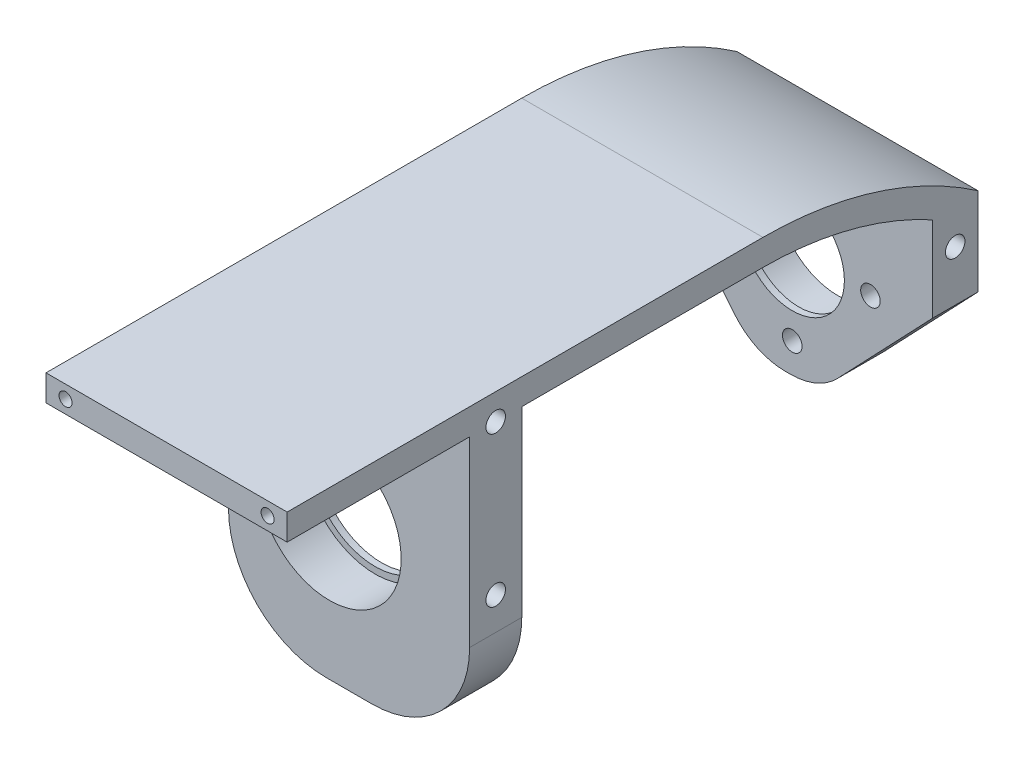
SolidWorks part; units mm, degrees
material "Polyetheretherketone (PEEK)"
ref_plane "Front Plane" through (0, 0, 0) normal (0, 0, 1) x (1, 0, 0)
ref_plane "Top Plane" through (0, 0, 0) normal (0, 1, 0) x (1, 0, 0)
ref_plane "Right Plane" through (0, 0, 0) normal (1, 0, 0) x (0, 0, -1)
sketch "Sketch3" plane through (0, 0, 0) normal (1, 0, 0) x (0, 0, -1)
  line L0 (0, 0) -> (73, 0)
  line L1 (0, 0) -> (0, -4)
  line L2 (0, -4) -> (73, -4)
  line L4 (113.6909, -22.5) -> (70.143, -22.5) construction
  line L6 (90.9961, -30.5) -> (104.9961, -30.5) construction
  line L7 (90.9961, -30.5) -> (90.9961, -14.5) construction
  line L8 (90.9961, -14.5) -> (104.9961, -14.5) construction
  line L9 (104.9961, -30.5) -> (104.9961, -14.5) construction
  line L10 (90.9961, -30.5) -> (104.9961, -14.5) construction
  line L11 (90.9961, -14.5) -> (104.9961, -30.5) construction
  line L13 (109.8205, -18.5) -> (115.4706, -18.5)
  arc A0 (73, 0) -> (115.4706, -18.5) centre (73, -58) cw
  arc A1 (73, -4) -> (104.9961, -14.5) centre (73, -58) cw
  arc A2 (104.9961, -14.5) -> (109.8205, -18.5) centre (73, -58) cw
  point P9 (97.9961, -22.5)
  dimension "D1" = 58
  dimension "D2" = 4
  dimension "D3" = 73
  dimension "D4" = 22.5
  dimension "D5" = 16
  dimension "D6" = 4
  dimension "D7" = 14
extrude "Boss-Extrude1" add sketch "Sketch3" along normal blind 37
ref_plane "Plane1" through (21.5, 0, 0) normal (1, 0, 0) x (0, 0, -1)
sketch "Sketch4" plane through (37, 0, 0) normal (1, 0, 0) x (0, 0, -1)
  line L0 (28, -4) -> (28, -14.5)
  line L1 (0, -4) -> (73, -4) construction
  line L2 (114.75, -23.7518) -> (114.75, -33.7153) construction
  line L3 (0, 0) -> (0, -4) construction
  line L4 (28, -4) -> (36, -4)
  line L5 (36, -4) -> (36, -15.5)
  line L6 (36, -15.5) -> (35, -15.5) construction
  line L7 (35, -15.5) -> (35, -14.5) construction
  line L8 (35, -14.5) -> (28, -14.5) construction
  line L9 (35, -15.5) -> (35, -25.5) construction
  line L10 (35, -25.5) -> (17.1507, -25.5) construction
  line L11 (28, -14.5) -> (28, -36.5)
  line L12 (36, -15.5) -> (36, -35.5)
  line L13 (28, -47) -> (36, -47)
  line L14 (28, -47) -> (28, -36.5)
  line L15 (36, -47) -> (36, -35.5)
  line L16 (73, 0) -> (0, 0) construction
  arc A0 (109.8205, -18.5) -> (73, -4) centre (73, -58) ccw construction
  point P22 (28, -25.5)
  point P23 (36, -25.5)
  dimension "D1" = 28
  dimension "D2" = 114.75
  dimension "D3" = 25.5
  dimension "D4" = 8
  dimension "D5" = 7
  dimension "D6" = 11.5
  dimension "D7" = 11
extrude "Boss-Extrude3" add sketch "Sketch4" against normal up to surface (37 mm away) contours L11 L14 L13 L15 L12 L5 L4 L0 up to face at (0, -6.1802, -62.4324)
sketch "Sketch5" plane through (0, 0, -28) normal (0, 0, 1) x (1, 0, 0)
  line L0 (37, -25.5) -> (21.5, -25.5) construction
  line L1 (37, -47) -> (37, -4) construction
  circle A0 centre (21.5, -25.5) radius 11
  dimension "D2" = 22
  dimension "D1" = 15.5
  dimension "D3" = 21.5
extrude "Cut-Extrude1" cut sketch "Sketch5" against normal blind 7
sketch "Sketch6" plane through (0, 0, -35) normal (0, 0, 1) x (1, 0, 0)
  circle A0 centre (21.5, -25.5) radius 10
  dimension "D1" = 20
extrude "Cut-Extrude2" cut sketch "Sketch6" against normal blind 7
sketch "Sketch7" plane through (37, 0, 0) normal (1, 0, 0) x (0, 0, -1)
  line L0 (36, -4) -> (99, -4) construction
  line L1 (99, -4) -> (99, -10.6714) construction
  line L2 (67.5, -4) -> (67.5, -25.5) construction
  line L3 (67.5, -25.5) -> (116.1248, -25.5) construction
  line L4 (99, -10.6714) -> (99, -16) construction
  line L5 (99, -16) -> (105, -16) construction
  line L6 (105, -16) -> (105, -17.5) construction
  line L7 (105, -17.5) -> (106, -17.5) construction
  line L8 (106, -17.5) -> (106, -15.2566) construction
  line L9 (99, -10.6714) -> (99, -47)
  line L10 (99, -47) -> (106, -47)
  line L11 (106, -47) -> (106, -15.2566)
  arc A0 (109.8205, -18.5) -> (73, -4) centre (73, -58) ccw construction
  arc A2 (106, -15.2566) -> (99, -10.6714) centre (73, -58) ccw
  dimension "D1" = 63
  dimension "D2" = 21.5
  dimension "D3" = 9.5
  dimension "D4" = 8
  dimension "D5" = 6
  dimension "D6" = 1
  dimension "D7" = 43
extrude "Boss-Extrude4" add sketch "Sketch7" against normal up to surface (37 mm away) contours L11 A2 L9 L10 up to face at (0, -13.9081, -50.2594)
sketch "Sketch8" plane through (0, 0, -106) normal (0, 0, 1) x (1, 0, 0)
  circle A0 centre (21.5, -25.5) radius 9.5
  dimension "D1" = 19
extrude "Cut-Extrude3" cut sketch "Sketch8" along normal blind 6
sketch "Sketch9" plane through (0, 0, -100) normal (0, 0, -1) x (-1, 0, 0)
  circle A0 centre (-21.5, -25.5) radius 8
  dimension "D1" = 16
extrude "Cut-Extrude4" cut sketch "Sketch9" against normal blind 1
sketch "Sketch10" plane through (0, 0, -106) normal (0, 0, -1) x (-1, 0, 0)
  line L0 (0, -23.7577) -> (-17.4711, -42.0819)
  line L1 (0, -47) -> (0, -15.2566) construction
  line L2 (-17.4711, -42.0819) -> (-27.3185, -42.0819)
  line L3 (-27.3185, -42.0819) -> (-37, -30.2284)
  line L4 (-37, -47) -> (-37, -15.2566) construction
  line L5 (-37, -30.2284) -> (-37, -47)
  line L6 (-37, -47) -> (0, -47)
  line L7 (0, -47) -> (0, -23.7577)
extrude "Cut-Extrude5" cut sketch "Sketch10" against normal up to surface (7 mm away) up to face at (13.5, -25.5, -99)
sketch "Sketch11" plane through (37, 0, 0) normal (1, 0, 0) x (0, 0, -1)
  line L0 (106, -15.2566) -> (106, -10.303)
  line L1 (109.8205, -18.5) -> (115.4706, -18.5) construction
  line L2 (109.8205, -18.5) -> (115.4706, -18.5)
  arc A0 (115.4706, -18.5) -> (73, 0) centre (73, -58) ccw construction
  arc A1 (109.8205, -18.5) -> (106, -15.2566) centre (73, -58) ccw construction
  arc A2 (109.8205, -18.5) -> (106, -15.2566) centre (73, -58) ccw
  arc A3 (115.4706, -18.5) -> (106, -10.303) centre (73, -58) ccw
extrude "Cut-Extrude6" cut sketch "Sketch11" against normal through all
fillet "Fillet2" radius 10 2 edges at (17.4711, -42.0819, -102.5) (27.3185, -42.0819, -102.5)
sketch "Sketch12" plane through (0, 0, -99) normal (0, 0, 1) x (1, 0, 0)
  line L0 (21.5, -25.5) -> (21.5, -13.5) construction
  circle A0 centre (21.5, -13.5) radius 1.5
  circle A1 centre (33.5, -25.5) radius 1.5
  circle A2 centre (21.5, -37.5) radius 1.5
  circle A3 centre (9.5, -25.5) radius 1.5
  point P12 (21.5, -25.5)
  dimension "D1" = 3
  dimension "D3" = 12
  dimension "D4" = 12
  dimension "D5" = 12
  dimension "D2" = 4
extrude "Cut-Extrude7" cut sketch "Sketch12" against normal through all
sketch "Sketch13" [suppressed] plane through (0, 0, -28) normal (0, 0, 1) x (1, 0, 0)
  line L0 (23, 0) -> (23, -32) construction
  line L1 (37, 0) -> (0, 0) construction
  line L3 (0, -47) -> (0, -4) construction
  circle A0 centre (23, -32) radius 11
  dimension "D2" = 22
  dimension "D1" = 32
  dimension "D3" = 23
extrude "Cut-Extrude8" [suppressed] cut sketch "Sketch13" against normal blind 7 contours A0
sketch "Sketch14" [suppressed] plane through (0, 0, -35) normal (0, 0, 1) x (1, 0, 0)
  circle A0 centre (23, -32) radius 10
  dimension "D1" = 20
extrude "Cut-Extrude9" [suppressed] cut sketch "Sketch14" against normal blind 7
sketch "Sketch15" [suppressed] plane through (0, 0, 0) normal (-1, 0, 0) x (0, 0, 1)
  line L0 (-94, -8.2506) -> (-94, -47)
  line L1 (-94, -47) -> (-101, -47)
  line L2 (-101, -47) -> (-101, -11.8264)
  line L3 (-36, -4) -> (-36, -47) construction
  line L4 (-28, -47) -> (-36, -47) construction
  arc A0 (-73, -4) -> (-109.8205, -18.5) centre (-73, -58) ccw construction
  arc A1 (-94, -8.2506) -> (-101, -11.8264) centre (-73, -58) ccw
  dimension "D1" = 58
  dimension "D2" = 7
extrude "Boss-Extrude5" [suppressed] add sketch "Sketch15" against normal up to surface (37 mm away)
sketch "Sketch16" [suppressed] plane through (0, 0, -94) normal (0, 0, 1) x (1, 0, 0)
  circle A0 centre (23, -32) radius 8
  dimension "D1" = 16
extrude "Cut-Extrude10" [suppressed] cut sketch "Sketch16" against normal blind 1
sketch "Sketch17" [suppressed] plane through (0, 0, -95) normal (0, 0, 1) x (1, 0, 0)
  circle A0 centre (23, -32) radius 9.5
  dimension "D1" = 19
extrude "Cut-Extrude11" [suppressed] cut sketch "Sketch17" against normal through all
sketch "Sketch18" [suppressed] plane through (37, 0, 0) normal (1, 0, 0) x (0, 0, -1)
  line L0 (101, -11.8264) -> (101, -7.2063)
  line L1 (109.8205, -18.5) -> (115.4706, -18.5) construction
  line L2 (109.8205, -18.5) -> (115.4706, -18.5)
  arc A0 (115.4706, -18.5) -> (73, 0) centre (73, -58) ccw construction
  arc A1 (109.8205, -18.5) -> (101, -11.8264) centre (73, -58) ccw construction
  arc A2 (115.4706, -18.5) -> (101, -7.2063) centre (73, -58) ccw
  arc A3 (109.8205, -18.5) -> (101, -11.8264) centre (73, -58) ccw
extrude "Cut-Extrude12" [suppressed] cut sketch "Sketch18" against normal through all
sketch "Sketch19" [suppressed] plane through (0, 0, -101) normal (0, 0, -1) x (-1, 0, 0)
  line L0 (-23, -32) -> (-23, -20) construction
  circle A0 centre (-23, -20) radius 1.5
  circle A1 centre (-11, -32) radius 1.5
  circle A2 centre (-23, -44) radius 1.5
  circle A3 centre (-35, -32) radius 1.5
  point P12 (-23, -32)
  dimension "D1" = 3
  dimension "D2" = 12
  dimension "D4" = 12
  dimension "D5" = 12
  dimension "D3" = 4
extrude "Cut-Extrude13" [suppressed] cut sketch "Sketch19" against normal up to surface (7 mm away)
fillet "Fillet3" [suppressed] radius 10
fillet "Fillet4" [suppressed] radius 10
fillet "Fillet5" radius 15 2 edges at (0, -47, -32) (37, -47, -32)
sketch "Sketch20" plane through (0, 0, 0) normal (-1, 0, 0) x (0, 0, 1)
  line L0 (-28, -4) -> (-36, -4) construction
  line L1 (-99, -10.6714) -> (-106, -10.6714) construction
  line L2 (-106, -23.7577) -> (-106, -10.303) construction
  line L3 (-102.5, -10.6714) -> (-102.5, -16) construction
  line L4 (-73, 0) -> (0, 0) construction
  line L5 (-32, -4) -> (-32, 0) construction
  line L6 (-32, -32) -> (-32, -27) construction
  line L7 (-36, -32) -> (-28, -32) construction
  line L8 (0, 0) -> (0, -4) construction
  circle A0 centre (-32, -4) radius 1.5
  circle A1 centre (-102.5, -16) radius 1.5
  circle A2 centre (-32, -27) radius 1.5
  dimension "D1" = 3
  dimension "D2" = 3
  dimension "D5" = 3
  dimension "D3" = 16
  dimension "D4" = 5
  dimension "D6" = 23
  dimension "D7" = 32
  dimension "D8" = 102.5
extrude "Cut-Extrude14" cut sketch "Sketch20" against normal blind 6
sketch "Sketch21" plane through (0, 0, 0) normal (0, 0, 1) x (1, 0, 0)
  line L0 (0, 0) -> (0, -4) construction
  line L1 (0, -2) -> (3, -2) construction
  line L2 (37, -2) -> (34, -2) construction
  line L3 (37, 0) -> (37, -4) construction
  circle A0 centre (3, -2) radius 1
  circle A1 centre (34, -2) radius 1
  dimension "D2" = 2
  dimension "D4" = 2
  dimension "D1" = 3
  dimension "D3" = 3
  dimension "D5" = 31
extrude "Cut-Extrude15" cut sketch "Sketch21" against normal blind 6 contours A0 | A1
sketch "Sketch22" [suppressed] plane through (0, 0, 0) normal (-1, 0, 0) x (0, 0, 1)
  line L0 (-94, -8.2506) -> (-101, -8.2506) construction
  line L1 (-101, -7.2063) -> (-101, -37) construction
  line L2 (-36, -4) -> (-28, -4) construction
  line L3 (-73, 0) -> (0, 0) construction
  circle A0 centre (-97.5, -16) radius 1.5
  circle A1 centre (-32, -4) radius 1.5
  circle A2 centre (-32, -27) radius 1.5
  point P7 (-97.5, -8.2506)
  dimension "D2" = 3
  dimension "D3" = 3
  dimension "D5" = 3
  dimension "D1" = 16
  dimension "D4" = 23
extrude "Cut-Extrude16" [suppressed] cut sketch "Sketch22" against normal blind 6
mirror "Mirror1" about plane through (37, -58, -73) normal (-1, 0, 0) of bodies 121
delete or keep bodies "Body-Delete/Keep 1" type delete bodies bodies 121
mirror "Mirror2" [suppressed]
delete or keep bodies "Body-Delete/Keep 2" [suppressed] type delete bodies bodies 122
equation "\"mini-flipper-shaft-diameter\"= 26mm"
equation "\"mini-shaft-ring-groove-diam\"= 7.8mm"
equation "\"mini-shaft-ring-groove-width\"= 1mm"
equation "\"dtCoverPlate-DistFrom-GearCent\"= 73mm"
equation "\"wormGearShaft-L\"= \"dtCoverPlate-DistFrom-GearCent\" - 27.75 + 3.75"
equation "\"wormGearShaft-Dsmall\"= 6mm"
equation "\"wormGearShaft-Dworm\"= 12mm"
equation "\"wormL-D\" = 12mm"
equation "\"wormR-D\" = 15mm"
equation "\"wormGearL-D\" = 40mm"
equation "\"wormGearR-D\" = 50mm"
